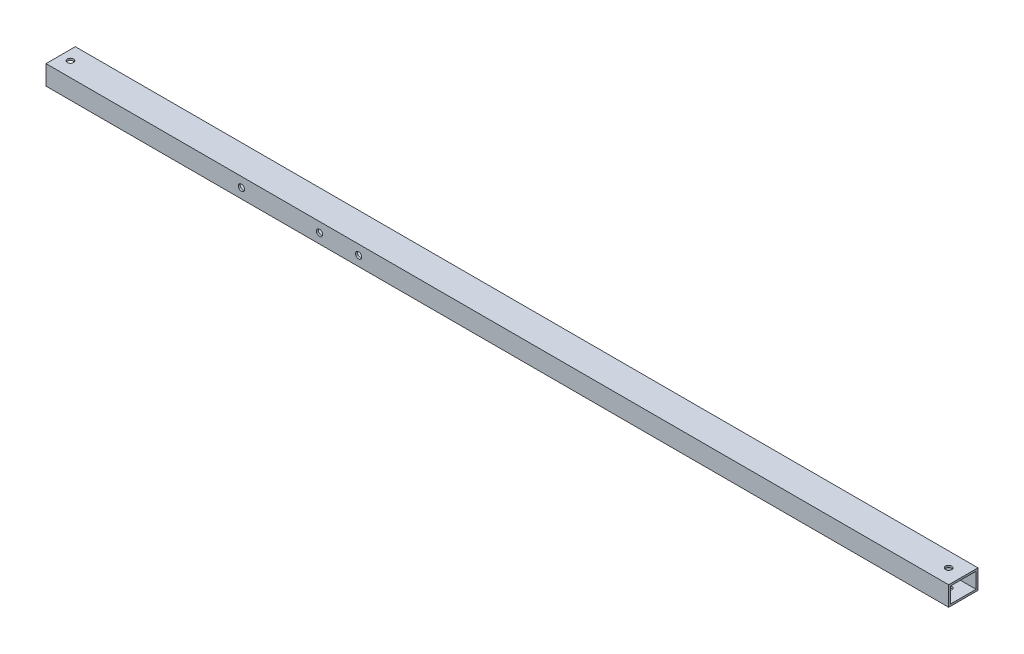
SolidWorks part; units mm, degrees
ref_plane "正面" through (0, 0, 0) normal (0, 0, 1) x (1, 0, 0)
ref_plane "平面" through (0, 0, 0) normal (0, 1, 0) x (1, 0, 0)
ref_plane "右側面" through (0, 0, 0) normal (1, 0, 0) x (0, 0, -1)
sketch "ｽｹｯﾁ1" plane through (0, 0, 0) normal (0, 0, 1) x (1, 0, 0)
  line L1 (-500, 5) -> (-720, 5)
  line L2 (-500, 5) -> (-500, -5)
  line L3 (-500, -5) -> (-720, -5)
  line L4 (-720, 5) -> (-720, -5)
  circle A3 centre (-620, 0) radius 1.6
  circle A4 centre (-580, 0) radius 1.6
  circle A5 centre (-560, 0) radius 1.6
  dimension "D1" = 5
  dimension "D5" = 120
  dimension "D6" = 80
  dimension "D7" = 60
  dimension "D2" = 220
  dimension "D3" = 5
  dimension "D4" = 5
extrude "ﾎﾞｽ - 押し出し1" add sketch "ｽｹｯﾁ1" along normal blind 15
sketch "ｽｹｯﾁ2" plane through (-500, 0, 0) normal (1, 0, 0) x (0, 0, -1)
  line L0 (0, -5) -> (0, 5) construction
  line L1 (-1, 4) -> (-14, 4)
  line L2 (-1, 4) -> (-1, -4)
  line L3 (-1, -4) -> (-14, -4)
  line L4 (-14, 4) -> (-14, -4)
  line L5 (-15, -5) -> (0, -5) construction
  line L6 (-15, -5) -> (-15, 5) construction
  line L7 (-15, 5) -> (0, 5) construction
  dimension "D1" = 1
  dimension "D2" = 1
  dimension "D3" = 1
  dimension "D4" = 1
extrude "ｶｯﾄ - 押し出し1" cut sketch "ｽｹｯﾁ2" against normal blind 2000
sketch "ｽｹｯﾁ3" plane through (0, -5, 0) normal (0, -1, 0) x (-1, 0, 0)
  line L0 (720, 0) -> (500, 0) construction
  line L1 (720, -15) -> (720, 0) construction
  circle A0 centre (715, -7.5) radius 1.6
  point P6 (720, -7.5)
  dimension "D1" = 7.5
  dimension "D2" = 5
  dimension "D3" = 3.2
extrude "ｶｯﾄ - 押し出し2" cut sketch "ｽｹｯﾁ3" against normal blind 1000
sketch "ｽｹｯﾁ4" plane through (-500, 0, 0) normal (1, 0, 0) x (0, 0, -1)
  line L1 (0, 5) -> (-15, 5)
  line L2 (0, 5) -> (0, -5)
  line L3 (0, -5) -> (-15, -5)
  line L4 (-15, 5) -> (-15, -5)
  line L5 (-1, 4) -> (-14, 4)
  line L6 (-1, 4) -> (-1, -4)
  line L7 (-1, -4) -> (-14, -4)
  line L8 (-14, 4) -> (-14, -4)
extrude "ﾎﾞｽ - 押し出し2" [suppressed] add sketch "ｽｹｯﾁ4" along normal blind 242
sketch "ｽｹｯﾁ5" [suppressed] plane through (0, -5, 0) normal (0, -1, 0) x (-1, 0, 0)
  line L0 (720, -15) -> (258, -15) construction
  line L1 (258, -15) -> (258, 0) construction
  circle A0 centre (265.5, -7.5) radius 1.6
  dimension "D1" = 7.5
  dimension "D2" = 7.5
  dimension "D3" = 3.2
extrude "ｶｯﾄ - 押し出し3" [suppressed] cut sketch "ｽｹｯﾁ5" against normal blind 240
ref_plane "平面1" through (-500, -5, 15) normal (1, 0, 0) x (0, 0, -1)
sketch "ｽｹｯﾁ7" plane through (0, -5, 0) normal (0, -1, 0) x (1, 0, 0)
  line L0 (-500, 15) -> (-500, 0)
  line L1 (-500, 0) -> (-258, 0)
  line L3 (-258, 0) -> (-258, 15)
  line L4 (-258, 15) -> (-500, 15)
  circle A2 centre (-265.5, 7.5) radius 1.6
  dimension "D1" = 7.5
  dimension "D2" = 7.5
  dimension "D3" = 3.2
  dimension "D4" = 242
extrude "ﾎﾞｽ - 押し出し3" add sketch "ｽｹｯﾁ7" against normal blind 10
sketch "ｽｹｯﾁ8" plane through (-720, 0, 0) normal (-1, 0, 0) x (0, 0, 1)
  line L14 (14, -4) -> (14, 4)
  line L15 (14, 4) -> (1, 4)
  line L16 (1, 4) -> (1, -4)
  line L17 (1, -4) -> (14, -4)
  line L18 (14, -4) -> (14, 4)
  line L19 (14, 4) -> (1, 4)
  line L20 (1, 4) -> (1, -4)
  line L21 (1, -4) -> (14, -4)
  dimension "D1" = 1
extrude "ｶｯﾄ - 押し出し4" cut sketch "ｽｹｯﾁ8" against normal blind 1000
